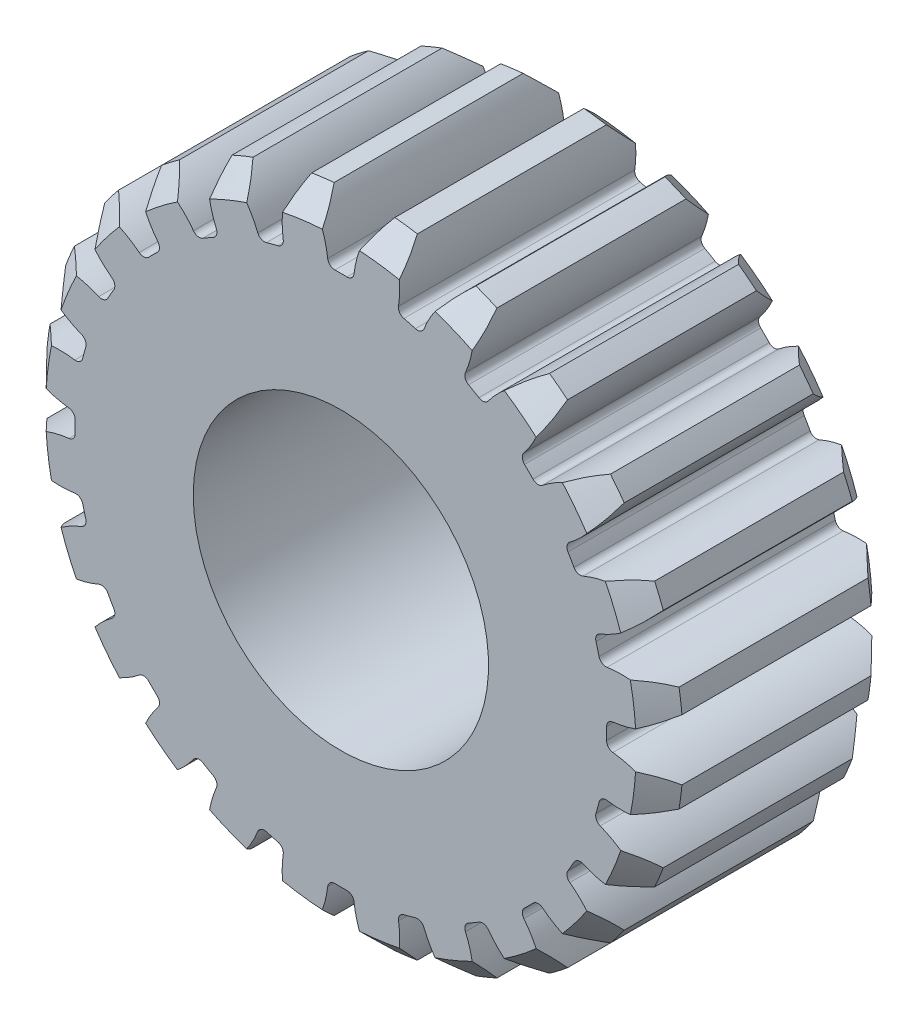
SolidWorks part; units mm, degrees
material "Plain Carbon Steel"
ref_plane "Front Plane" through (0, 0, 0) normal (0, 0, 1) x (1, 0, 0)
ref_plane "Top Plane" through (0, 0, 0) normal (0, 1, 0) x (1, 0, 0)
ref_plane "Right Plane" through (0, 0, 0) normal (1, 0, 0) x (0, 0, -1)
sketch "Sketch1" plane through (0, 0, 0) normal (0, 0, 1) x (1, 0, 0)
  circle A0 centre (0, 0) radius 25 construction
  circle A1 centre (0, 0) radius 27
  dimension "D1" = 50
  dimension "D2" = 54
extrude "Boss-Extrude1" add sketch "Sketch1" along normal mid plane 20
sketch "Sketch2" plane through (0, 0, 0) normal (0, 0, 1) x (1, 0, 0)
  line L0 (0, 27) -> (0, 0) construction
  line L1 (0, 0) -> (6.7146, 26.1517) construction
  line L2 (0, 0) -> (3.384, 26.7871) construction
  line L3 (-1.072, 22.4744) -> (0, 0) construction
  line L4 (-1.5698, 24.9507) -> (1.5698, 24.9507) construction
  line L5 (1.5698, 24.9507) -> (4.6845, 24.5572) construction
  line L6 (-2.2805, 26.9035) -> (0, 20.6378) construction
  arc A0 (1.072, 22.4744) -> (-1.072, 22.4744) centre (0, 0) ccw
  circle A1 centre (0, 0) radius 23 construction
  circle A2 centre (0, 0) radius 27 construction
  arc A3 (-2.5691, 26.8775) -> (-1.072, 22.4744) centre (-9.4743, 22.0737) cw
  circle A4 centre (0, 0) radius 27 construction
  arc A5 (2.5691, 26.8775) -> (1.072, 22.4744) centre (9.4743, 22.0737) ccw
  circle A6 centre (0, 0) radius 25 construction
  arc A7 (2.5691, 26.8775) -> (-2.5691, 26.8775) centre (0, 0) ccw
  point P23 (0, 21.0287)
  point P24 (0, 0)
  dimension "D1" = 14.4
  dimension "D2" = 4
  dimension "D3" = 4.5
  dimension "D4" = 20
extrude "Cut-Extrude4" cut sketch "Sketch2" against normal through all both and the other way through all
fillet "Fillet1" radius 0.6 2 edges at (1.072, 22.4744, 0) (-1.072, 22.4744, 0)
chamfer "Chamfer1" distance 2 2 edges at (0, -27, -10) (0, -27, 10)
pattern_circular "CirPattern1" count 25 every 15 about axis through (0, 0, 0) along (0, 0, 1) of "Fillet1", "Cut-Extrude4"
sketch "Sketch3" plane through (0, 0, -10) normal (0, 0, -1) x (-1, 0, 0)
  circle A0 centre (0, 0) radius 12.5
  dimension "D1" = 25
extrude "Cut-Extrude6" cut sketch "Sketch3" against normal through all
equation "\"module\"= 2"
equation "\"number_of_teeth\"= 25"
equation "\"pressure_angle\"= 20"
equation "\"D3@Sketch2\"=\"module\" * if(\"module\" => 1.25,2.25,2.4)"
equation "\"D4@Sketch2\"=\"pressure_angle\""
equation "\"D1@Fillet1\"=0.3 * \"module\""
equation "\"D1@CirPattern1\"=\"number_of_teeth\""
equation "\"D1@Chamfer1\"=\"module\""
